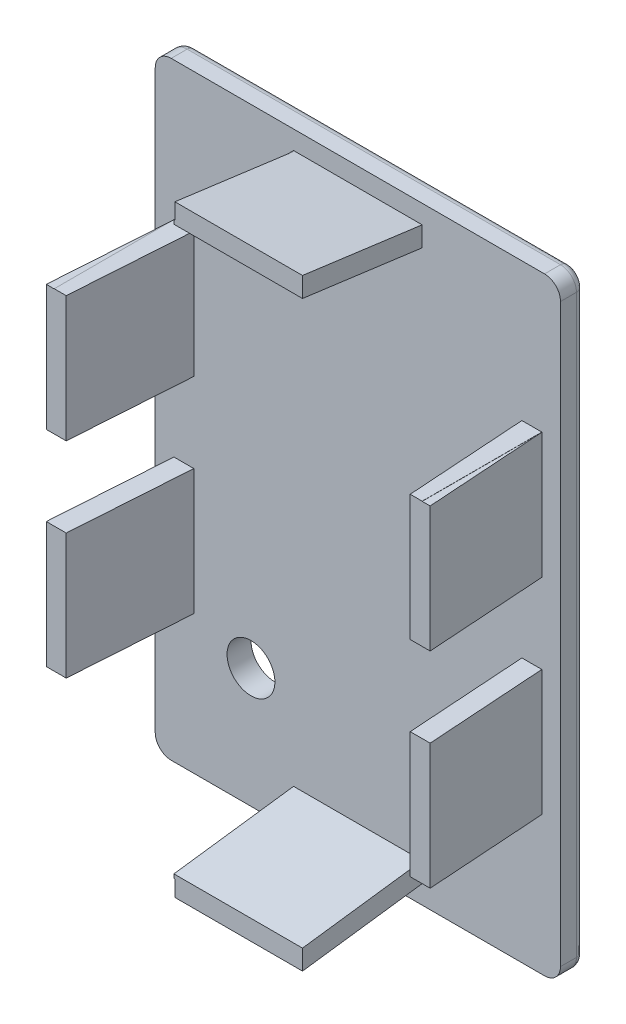
SolidWorks part; units mm, degrees
material "PLA"
ref_plane "Alzado" through (0, 0, 0) normal (0, 0, 1) x (1, 0, 0)
ref_plane "Planta" through (0, 0, 0) normal (0, 1, 0) x (1, 0, 0)
ref_plane "Vista lateral" through (0, 0, 0) normal (1, 0, 0) x (0, 0, -1)
sketch "Croquis1" plane through (0, 0, 0) normal (0, 0, 1) x (1, 0, 0)
  line L1 (25.4, 38.1) -> (-25.4, 38.1)
  line L2 (25.4, 38.1) -> (25.4, -38.1)
  line L3 (25.4, -38.1) -> (-25.4, -38.1)
  line L4 (-25.4, 38.1) -> (-25.4, -38.1)
  line L5 (25.4, 38.1) -> (-25.4, -38.1) construction
  line L6 (25.4, -38.1) -> (-25.4, 38.1) construction
  point P0 (0, 0)
  dimension "D1" = 76.2
  dimension "D2" = 50.8
extrude "Saliente-Extruir1" add sketch "Croquis1" along normal blind 18
sketch "Croquis2" plane through (0, 0, 18) normal (0, 0, 1) x (1, 0, 0)
  line L0 (25.4, 38.1) -> (-25.4, 38.1) construction
  line L1 (-23.06, 35.76) -> (23.06, 35.76)
  line L2 (-23.06, 35.76) -> (-23.06, -35.76)
  line L3 (-23.06, -35.76) -> (23.06, -35.76)
  line L4 (23.06, 35.76) -> (23.06, -35.76)
  line L5 (-25.4, -38.1) -> (25.4, -38.1) construction
  line L6 (-25.4, 38.1) -> (-25.4, -38.1) construction
  line L7 (25.4, -38.1) -> (25.4, 38.1) construction
  line L9 (-25.4, 38.1) -> (25.4, 38.1)
  line L10 (-25.4, 38.1) -> (-25.4, -38.1)
  line L11 (-25.4, -38.1) -> (25.4, -38.1)
  line L12 (25.4, 38.1) -> (25.4, -38.1)
  line L13 (-19.4, 32.1) -> (19.4, 32.1)
  line L14 (-19.4, 32.1) -> (-19.4, -32.1)
  line L15 (-19.4, -32.1) -> (19.4, -32.1)
  line L16 (19.4, 32.1) -> (19.4, -32.1)
  line M9 (-25.4, 38.1) -> (-25.4, -38.1)
  line M10 (-25.4, -38.1) -> (25.4, -38.1)
  line M11 (25.4, -38.1) -> (25.4, 38.1)
  line M12 (25.4, 38.1) -> (-25.4, 38.1)
  dimension "D1" = 2.34
  dimension "D2" = 2.34
  dimension "D3" = 2.34
  dimension "D4" = 2.34
  dimension "D5" = 6
  dimension "D6" = 6
  dimension "D7" = 6
  dimension "D8" = 6
extrude "Cortar-Extruir1" cut sketch "Croquis2" against normal blind 15 contours L1 L4 L3 L2 M12 M9 M10 M11 | L16 L13 L14 L15
sketch "Croquis3" plane through (0, 0, 18) normal (0, 0, 1) x (1, 0, 0)
  line L0 (-23.06, 35.76) -> (-23.06, -35.76) construction
  line L1 (-23.06, 22.1) -> (-19.4, 22.1)
  line L2 (-23.06, 22.1) -> (-23.06, -22.1)
  line L3 (-23.06, -22.1) -> (-19.4, -22.1)
  line L4 (-19.4, 22.1) -> (-19.4, -22.1)
  line L5 (-19.4, 32.1) -> (-19.4, -32.1) construction
  line L6 (-19.4, -32.1) -> (19.4, -32.1) construction
  line L7 (-9.4, -32.1) -> (9.3837, -32.1)
  line L8 (-9.4, -32.1) -> (-9.4, -35.76)
  line L9 (-9.4, -35.76) -> (9.3837, -35.76)
  line L10 (9.3837, -32.1) -> (9.3837, -35.76)
  line L11 (-23.06, -35.76) -> (23.06, -35.76) construction
  line L12 (19.4, 32.1) -> (19.4, -32.1) construction
  line L13 (19.4, -22.1) -> (23.06, -22.1)
  line L14 (19.4, -22.1) -> (19.4, 22.1)
  line L15 (19.4, 22.1) -> (23.06, 22.1)
  line L16 (23.06, -22.1) -> (23.06, 22.1)
  line L17 (23.06, 35.76) -> (23.06, -35.76) construction
  line L18 (-23.06, 35.76) -> (23.06, 35.76) construction
  line L19 (-9.4, 35.76) -> (9.4, 35.76)
  line L20 (-9.4, 35.76) -> (-9.4, 32.1)
  line L21 (-9.4, 32.1) -> (9.4, 32.1)
  line L22 (9.4, 35.76) -> (9.4, 32.1)
  line L23 (-19.4, 32.1) -> (19.4, 32.1) construction
  line L24 (-19.4, 32.1) -> (-19.4, -32.1) construction
  line L25 (19.4, 32.1) -> (19.4, -32.1) construction
  dimension "D1" = 10
  dimension "D2" = 10
  dimension "D3" = 10
  dimension "D4" = 10
  dimension "D5" = 10
  dimension "D6" = 10
  dimension "D7" = 10
extrude "Cortar-Extruir2" [suppressed] cut sketch "Croquis3" against normal blind 7
fillet "Redondeo1" [suppressed] radius 2
fillet "Redondeo2" [suppressed] radius 1
sketch "Croquis5" [suppressed] plane through (0, -38.1, 0) normal (0, -1, 0) x (1, 0, 0)
  line L0 (-23.4, 3) -> (23.4, 3) construction
  line L1 (-3, 3) -> (3, 3)
  line L2 (-3, 3) -> (-3, 1.5)
  line L3 (-3, 1.5) -> (3, 1.5)
  line L4 (3, 3) -> (3, 1.5)
  line L5 (0, 1) -> (0, 3) construction
  line L6 (-23.4, 1) -> (23.4, 1) construction
  dimension "D1" = 3
  dimension "D2" = 3
  dimension "D3" = 1.5
extrude "Cortar-Extruir4" [suppressed] cut sketch "Croquis5" against normal blind 6
sketch "Croquis6" plane through (0, 0, 18) normal (0, 0, 1) x (1, 0, 0)
  line L0 (-23.06, 35.76) -> (-8.06, 35.76)
  line L1 (-23.06, 35.76) -> (23.06, 35.76) construction
  line L2 (-8.06, 35.76) -> (-8.06, 32.1)
  line L3 (-19.4, 32.1) -> (19.4, 32.1) construction
  line L4 (-8.06, 32.1) -> (-19.4, 32.1)
  line L5 (-19.4, 32.1) -> (-19.4, 20.76)
  line L6 (-19.4, 32.1) -> (-19.4, -32.1) construction
  line L7 (-19.4, 20.76) -> (-23.06, 20.76)
  line L8 (-23.06, 35.76) -> (-23.06, -35.76) construction
  line L9 (-23.06, 20.76) -> (-23.06, 35.76)
  line L10 (23.06, 35.76) -> (8.06, 35.76)
  line L11 (-23.06, 35.76) -> (23.06, 35.76) construction
  line L12 (8.06, 35.76) -> (8.06, 32.1)
  line L13 (8.06, 32.1) -> (19.4, 32.1)
  line L14 (19.4, 32.1) -> (19.4, -32.1) construction
  line L15 (19.4, 32.1) -> (19.4, -32.1) construction
  line L16 (19.4, 32.1) -> (19.4, 20.76)
  line L17 (19.4, 20.76) -> (23.06, 20.76)
  line L18 (23.06, 35.76) -> (23.06, -35.76) construction
  line L19 (23.06, 20.76) -> (23.06, 35.76)
  line L20 (-23.06, -35.76) -> (-23.06, -20.76)
  line L21 (-23.06, 35.76) -> (-23.06, -35.76) construction
  line L22 (-23.06, -20.76) -> (-19.4, -20.76)
  line L23 (-19.4, 32.1) -> (-19.4, -32.1) construction
  line L24 (-19.4, -20.76) -> (-19.4, -32.1)
  line L25 (-19.4, -32.1) -> (-8.06, -32.1)
  line L26 (-19.4, -32.1) -> (19.4, -32.1) construction
  line L27 (-8.06, -32.1) -> (-8.06, -35.76)
  line L28 (-23.06, -35.76) -> (23.06, -35.76) construction
  line L29 (-8.06, -35.76) -> (-23.06, -35.76)
  line L30 (23.06, -35.76) -> (8.06, -35.76)
  line L31 (-23.06, -35.76) -> (23.06, -35.76) construction
  line L32 (8.06, -35.76) -> (8.06, -32.1)
  line L33 (-19.4, -32.1) -> (19.4, -32.1) construction
  line L34 (8.06, -32.1) -> (19.4, -32.1)
  line L35 (19.4, -32.1) -> (19.4, -20.76)
  line L36 (19.4, -20.76) -> (23.06, -20.76)
  line L37 (23.06, 35.76) -> (23.06, -35.76) construction
  line L38 (23.06, -20.76) -> (23.06, -35.76)
  dimension "D1" = 15
  dimension "D2" = 15
  dimension "D3" = 15
  dimension "D4" = 15
  dimension "D5" = 15
  dimension "D6" = 15
  dimension "D7" = 15
  dimension "D8" = 15
extrude "Cortar-Extruir8" cut sketch "Croquis6" against normal blind 15
sketch "Croquis10" plane through (0, -20.76, 0) normal (0, -1, 0) x (-1, 0, 0)
  line L0 (23.06, -18) -> (24.06, -18)
  line L1 (24.06, -18) -> (23.06, -3)
  line L2 (23.06, -3) -> (23.06, -18)
  line L3 (-23.06, -18) -> (-24.06, -18)
  line L4 (-24.06, -18) -> (-23.06, -3)
  line L5 (-23.06, -3) -> (-23.06, -18)
  dimension "D1" = 1
  dimension "D2" = 1
extrude "Saliente-Extruir3" add sketch "Croquis10" against normal blind 41.5
sketch "Croquis11" plane through (0, -20.76, 0) normal (0, -1, 0) x (1, 0, 0)
  line L0 (-19.4, 18) -> (-21.56, 18)
  line L1 (-19.4, 18) -> (-24.06, 18) construction
  line L2 (-21.56, 18) -> (-20.56, 3)
  line L3 (-19.4, 3) -> (-23.06, 3) construction
  line L4 (-20.56, 3) -> (-19.4, 3)
  line L5 (-19.4, 18) -> (-19.4, 3)
  dimension "D1" = 2.5
  dimension "D2" = 1.16
extrude "Cortar-Extruir9" cut sketch "Croquis11" against normal blind 51.5
sketch "Croquis12" plane through (0, -20.76, 0) normal (0, -1, 0) x (1, 0, 0)
  line L0 (19.4, 18) -> (19.4, 3)
  line L1 (19.4, 3) -> (20.56, 3)
  line L2 (23.06, 3) -> (19.4, 3) construction
  line L3 (20.56, 3) -> (21.56, 18)
  line L4 (24.06, 18) -> (19.4, 18) construction
  line L5 (21.56, 18) -> (19.4, 18)
  dimension "D1" = 2.5
  dimension "D2" = 1.16
extrude "Cortar-Extruir10" cut sketch "Croquis12" against normal blind 51.5
sketch "Croquis13" plane through (8.06, 0, 0) normal (1, 0, 0) x (0, 0, -1)
  line L0 (-18, -35.76) -> (-18, -37.76)
  line L1 (-18, -37.76) -> (-3, -35.76)
  line L2 (-3, -35.76) -> (-18, -35.76)
  line L3 (-18, 35.76) -> (-18, 37.76)
  line L4 (-18, 37.76) -> (-3, 35.76)
  line L5 (-3, 35.76) -> (-18, 35.76)
  dimension "D1" = 2
  dimension "D2" = 2
extrude "Saliente-Extruir4" add sketch "Croquis13" against normal blind 16
sketch "Croquis14" plane through (8.06, 0, 0) normal (1, 0, 0) x (0, 0, -1)
  line L0 (-3, -32.1) -> (-18, -32.1)
  line L1 (-18, -32.1) -> (-18, -35.26)
  line L2 (-18, -32.1) -> (-18, -37.76) construction
  line L3 (-18, -35.26) -> (-3, -33.26)
  line L4 (-3, -32.1) -> (-3, -35.76) construction
  line L5 (-3, -33.26) -> (-3, -32.1)
  line L6 (-18, 32.1) -> (-18, 35.26)
  line L7 (-18, 37.76) -> (-18, 32.1) construction
  line L8 (-18, 35.26) -> (-3, 33.26)
  line L9 (-3, 35.76) -> (-3, 32.1) construction
  line L10 (-3, 33.26) -> (-3, 32.1)
  line L11 (-3, 32.1) -> (-18, 32.1)
  dimension "D1" = 2.5
  dimension "D2" = 1.16
  dimension "D3" = 2.5
  dimension "D4" = 1.16
extrude "Cortar-Extruir11" cut sketch "Croquis14" against normal blind 16.5
fillet "Redondeo3" radius 2 4 edges at (25.4, 38.1, 1.5) (-25.4, 38.1, 1.5) (-25.4, -38.1, 1.5) (25.4, -38.1, 1.5)
fillet "Redondeo4" radius 1 8 edges at (-24.8142, 37.5142, 0) (-25.4, 0, 0) (-24.8142, -37.5142, 0) (0, -38.1, 0) (24.8142, -37.5142, 0) (25.4, 0, 0) (24.8142, 37.5142, 0) (0, 38.1, 0)
sketch "Croquis15" plane through (0, 0, 18) normal (0, 0, 1) x (1, 0, 0)
  line L0 (-24.06, -0.01) -> (24.06, -0.01) construction
  line L1 (-24.06, 20.74) -> (-24.06, -20.76) construction
  line L2 (24.06, 20.74) -> (24.06, -20.76) construction
  line L4 (-24.06, 4.99) -> (24.06, 4.99)
  line L5 (-24.06, 4.99) -> (-24.06, -5.01)
  line L6 (-24.06, -5.01) -> (24.06, -5.01)
  line L7 (24.06, 4.99) -> (24.06, -5.01)
  dimension "D1" = 5
  dimension "D2" = 5
extrude "Cortar-Extruir12" cut sketch "Croquis15" against normal blind 15
sketch "Croquis16" plane through (0, -38.1, 0) normal (0, -1, 0) x (1, 0, 0)
  line L0 (-23.4, 3) -> (23.4, 3) construction
  line L1 (-4, 3) -> (4, 3)
  line L2 (-4, 3) -> (-4, 1.5)
  line L3 (-4, 1.5) -> (4, 1.5)
  line L4 (4, 3) -> (4, 1.5)
  dimension "D1" = 1.5
  dimension "D2" = 8
  dimension "D3" = 4
extrude "Cortar-Extruir13" cut sketch "Croquis16" against normal blind 2
sketch "Croquis17" plane through (0, 0, 3) normal (0, 0, 1) x (1, 0, 0)
  line L0 (-25.4, 36.1) -> (-25.4, -36.1) construction
  line L1 (-23.4, -38.1) -> (-4, -38.1) construction
  circle A0 centre (-13.4, -23.1) radius 3
  dimension "D3" = 6
  dimension "D1" = 12
  dimension "D2" = 15
extrude "Cortar-Extruir14" cut sketch "Croquis17" against normal blind 10
